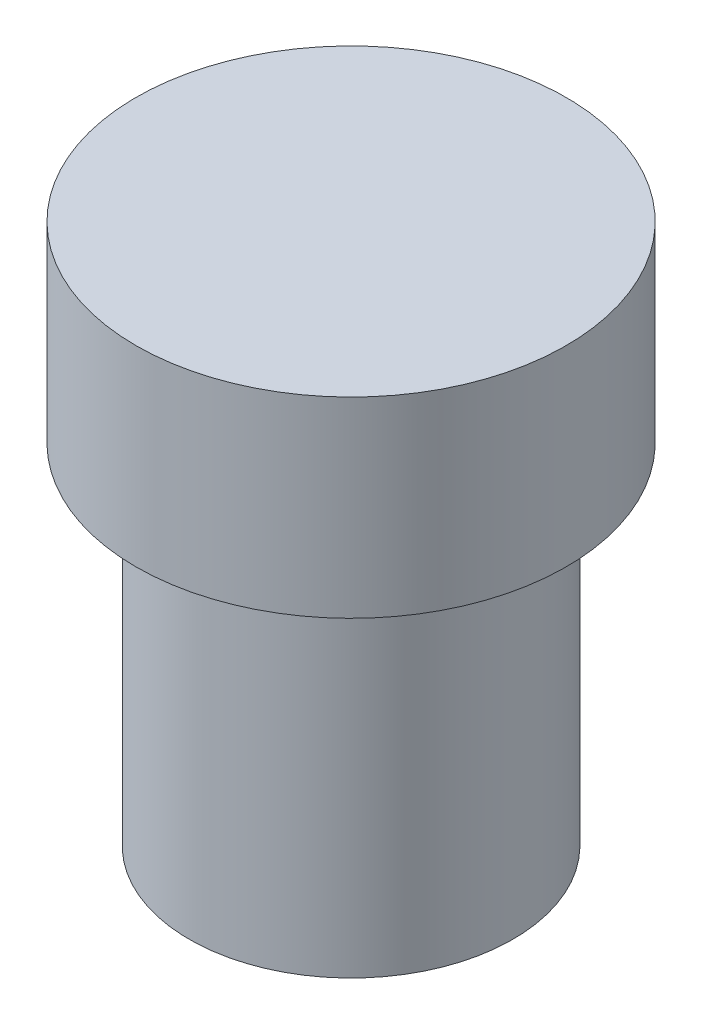
SolidWorks part; units mm, degrees
ref_plane "Front" through (0, 0, 0) normal (0, 0, 1) x (1, 0, 0)
ref_plane "Top" through (0, 0, 0) normal (0, 1, 0) x (1, 0, 0)
ref_plane "Right" through (0, 0, 0) normal (1, 0, 0) x (0, 0, -1)
sketch "Esboço1" plane through (0, 0, 0) normal (0, 1, 0) x (1, 0, 0)
  circle A0 centre (0, 0) radius 5.05
  dimension "D1" = 10.1
extrude "Ressalto-extrusão1" add sketch "Esboço1" along normal blind 4.5
sketch "Esboço2" plane through (0, 0, 0) normal (0, -1, 0) x (1, 0, 0)
  circle A0 centre (0, 0) radius 3.8
  dimension "D1" = 7.6
extrude "Ressalto-extrusão2" add sketch "Esboço2" along normal blind 8.2
